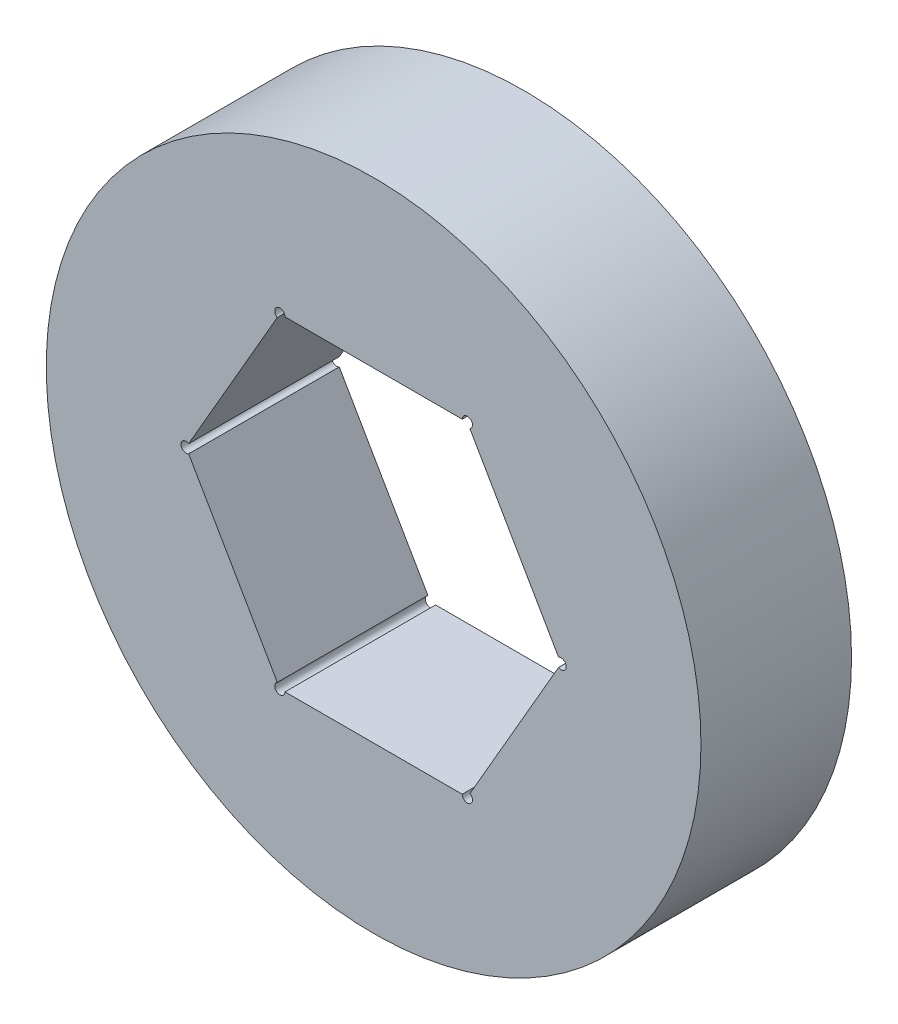
SolidWorks part; units mm, degrees
ref_plane "Front Plane" through (0, 0, 0) normal (0, 0, 1) x (1, 0, 0)
ref_plane "Top Plane" through (0, 0, 0) normal (0, 1, 0) x (1, 0, 0)
ref_plane "Right Plane" through (0, 0, 0) normal (1, 0, 0) x (0, 0, -1)
sketch "Sketch1" plane through (0, 0, 0) normal (0, 0, 1) x (1, 0, 0)
  line L1 (-7.2746, 0) -> (-3.6373, -6.3)
  line L2 (-3.6373, -6.3) -> (3.6373, -6.3)
  line L3 (3.6373, -6.3) -> (7.2746, 0)
  line L4 (7.2746, 0) -> (3.6373, 6.3)
  line L5 (3.6373, 6.3) -> (-3.6373, 6.3)
  line L6 (-3.6373, 6.3) -> (-7.2746, 0)
  circle A0 centre (0, 0) radius 12.7
  circle A1 centre (0, 0) radius 6.3 construction
  dimension "D1" = 25.4
  dimension "D2" = 12.6
extrude "Boss-Extrude1" add sketch "Sketch1" along normal blind 5.842
sketch "Sketch2" plane through (0, 0, 5.842) normal (0, 0, 1) x (1, 0, 0)
  circle A0 centre (3.6373, 6.3) radius 0.1984
  circle A1 centre (-3.6373, 6.3) radius 0.1984
  circle A2 centre (-7.2746, 0) radius 0.1984
  circle A3 centre (-3.6373, -6.3) radius 0.1984
  circle A4 centre (3.6373, -6.3) radius 0.1984
  circle A5 centre (7.2746, 0) radius 0.1984
  dimension "D1" = 0.3969
  dimension "D2" = 0.3969
  dimension "D3" = 0.3969
  dimension "D4" = 0.3969
  dimension "D5" = 0.3969
  dimension "D6" = 0.3969
extrude "Cut-Extrude1" cut sketch "Sketch2" against normal through all
